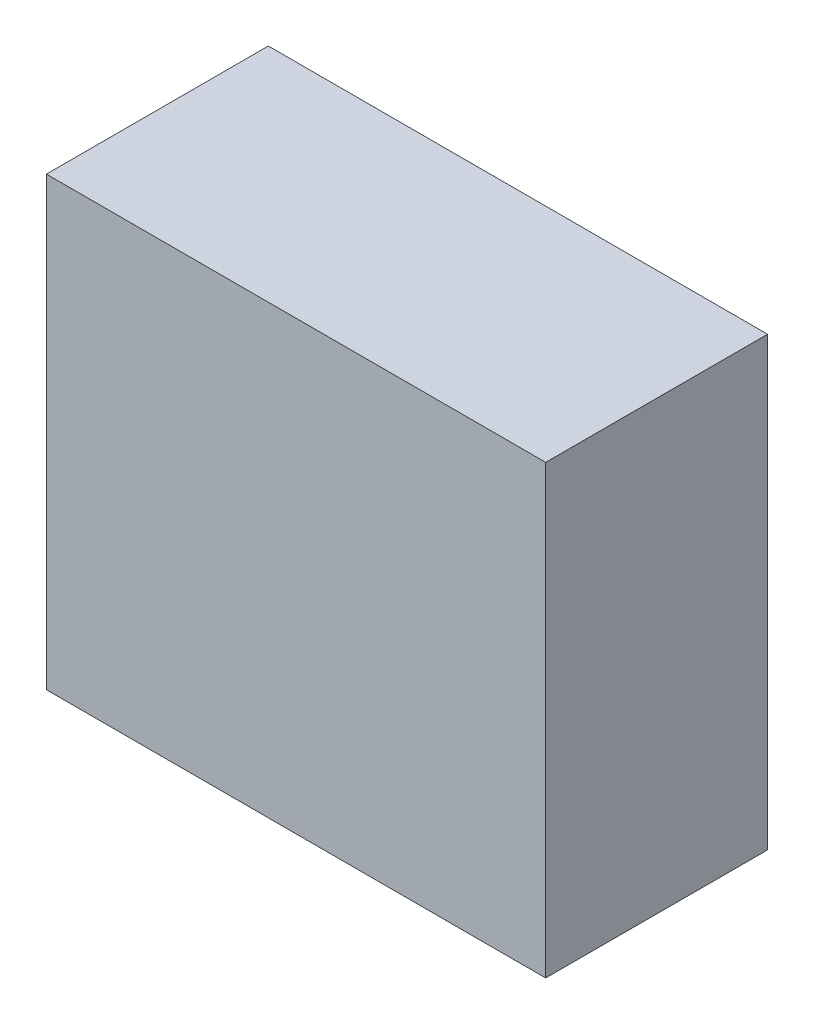
SolidWorks part; units mm, degrees
ref_plane "Front Plane" through (0, 0, 0) normal (0, 0, 1) x (1, 0, 0)
ref_plane "Top Plane" through (0, 0, 0) normal (0, 1, 0) x (1, 0, 0)
ref_plane "Right Plane" through (0, 0, 0) normal (1, 0, 0) x (0, 0, -1)
sketch "Sketch1" plane through (0, 0, 0) normal (0, 1, 0) x (1, 0, 0)
  line L1 (0, 0) -> (45.72, 0)
  line L2 (0, 0) -> (0, 20.32)
  line L3 (0, 20.32) -> (45.72, 20.32)
  line L4 (45.72, 0) -> (45.72, 20.32)
  dimension "D1" = 45.72
  dimension "D2" = 20.32
extrude "Boss-Extrude1" add sketch "Sketch1" along normal blind 40.894
